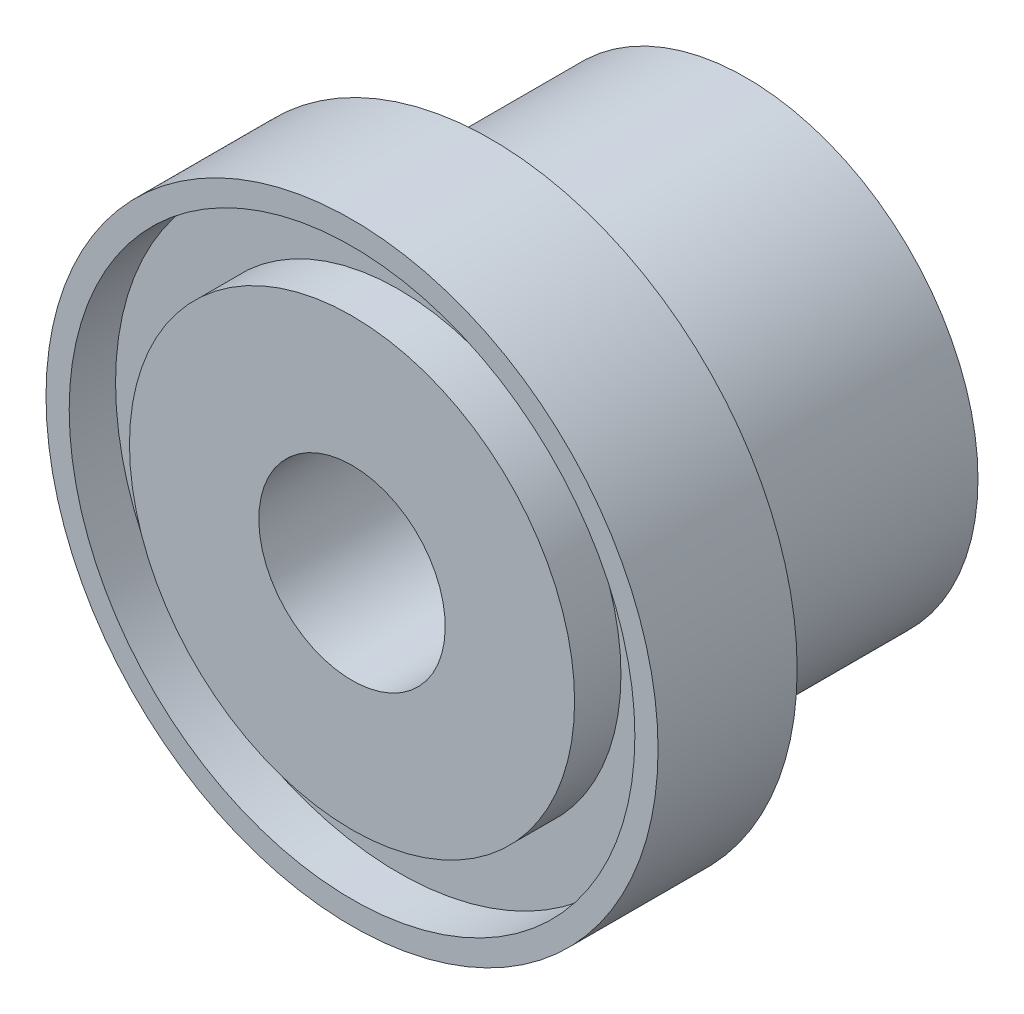
SolidWorks part; units mm, degrees
ref_plane "Front Plane" through (0, 0, 0) normal (0, 0, 1) x (1, 0, 0)
ref_plane "Top Plane" through (0, 0, 0) normal (0, 1, 0) x (1, 0, 0)
ref_plane "Right Plane" through (0, 0, 0) normal (1, 0, 0) x (0, 0, -1)
sketch "Sketch1" plane through (0, 0, 0) normal (0, 0, 1) x (1, 0, 0)
  circle A0 centre (43.1743, 8.5503) radius 6.35
  dimension "D2" = 12.7
extrude "Boss-Extrude1" add sketch "Sketch1" against normal up to surface (6.985 mm away)
sketch "Sketch3" plane through (0, 0, 0) normal (0, 0, 1) x (1, 0, 0)
  circle A0 centre (43.1743, 8.5503) radius 8.382
  dimension "D1" = 16.764
extrude "Boss-Extrude2" add sketch "Sketch3" along normal blind 3.81
sketch "Sketch5" plane through (0, 0, -6.985) normal (0, 0, -1) x (-1, 0, 0)
  circle A0 centre (-43.1743, 8.5503) radius 2.5527
extrude "Cut-Extrude2" cut sketch "Sketch5" against normal through all
sketch "Sketch6" plane through (0, 0, 3.81) normal (0, 0, 1) x (1, 0, 0)
  circle A0 centre (43.1743, 8.5503) radius 7.747
  circle A1 centre (43.1743, 8.5503) radius 6.096
  dimension "D1" = 15.494
  dimension "D2" = 12.192
extrude "Cut-Extrude3" cut sketch "Sketch6" against normal blind 1.27
